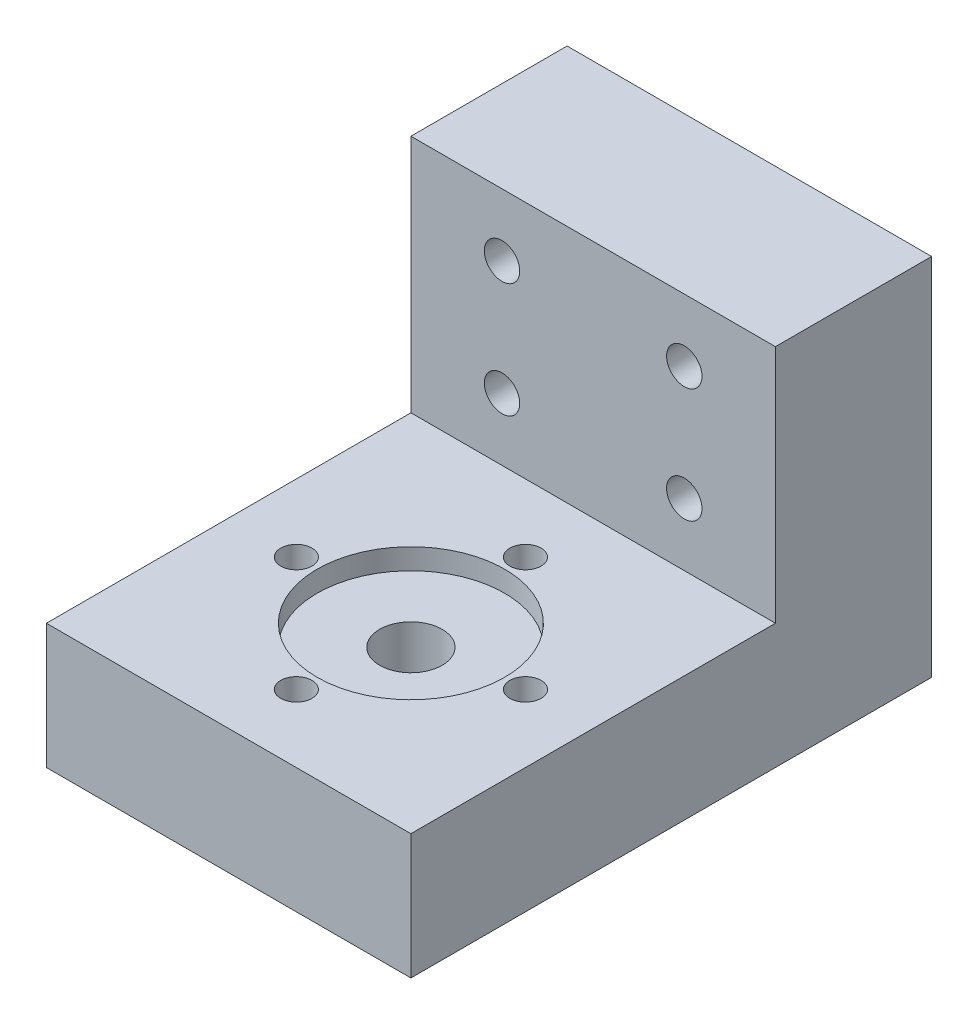
SolidWorks part; units mm, degrees
material "PET"
ref_plane "Front Plane" through (0, 0, 0) normal (0, 0, 1) x (1, 0, 0)
ref_plane "Top Plane" through (0, 0, 0) normal (0, 1, 0) x (1, 0, 0)
ref_plane "Right Plane" through (0, 0, 0) normal (1, 0, 0) x (0, 0, -1)
sketch "Sketch2" plane through (0, 0, 0) normal (0, 0, 1) x (1, 0, 0)
  line L1 (-17.5, -17.5) -> (17.5, -17.5)
  line L2 (-17.5, -17.5) -> (-17.5, 17.5)
  line L3 (-17.5, 17.5) -> (17.5, 17.5)
  line L4 (17.5, -17.5) -> (17.5, 17.5)
  line L5 (-17.5, -17.5) -> (17.5, 17.5) construction
  line L6 (-17.5, 17.5) -> (17.5, -17.5) construction
  point P0 (0, 0)
  dimension "D1" = 35
  dimension "D2" = 35
extrude "Boss-Extrude1" add sketch "Sketch2" along normal blind 15
sketch "Sketch3" plane through (0, 0, 15) normal (0, 0, 1) x (1, 0, 0)
  line L0 (17.5, -17.5) -> (17.5, 17.5) construction
  line L1 (-17.5, -17.5) -> (17.5, -17.5)
  line L2 (-17.5, -17.5) -> (-17.5, -5.5)
  line L3 (-17.5, -5.5) -> (17.5, -5.5)
  line L4 (17.5, -17.5) -> (17.5, -5.5)
  dimension "D1" = 12
extrude "Boss-Extrude2" add sketch "Sketch3" along normal blind 35
sketch "Sketch4" plane through (0, -5.5, 0) normal (0, 1, 0) x (1, 0, 0)
  circle A0 centre (0, -32.5) radius 9
  dimension "D1" = 18
extrude "Cut-Extrude1" cut sketch "Sketch4" against normal blind 2
sketch "Sketch5" plane through (0, -7.5, 0) normal (0, 1, 0) x (1, 0, 0)
  circle A0 centre (0, -32.5) radius 3
  dimension "D1" = 6
extrude "Cut-Extrude2" cut sketch "Sketch5" against normal blind 14
sketch "Sketch6" plane through (0, -5.5, 0) normal (0, 1, 0) x (1, 0, 0)
  line L0 (-11, -32.5) -> (11, -32.5) construction
  line L1 (0, -21.5) -> (0, -43.5) construction
  circle A0 centre (0, -32.5) radius 11 construction
  circle A1 centre (0, -21.5) radius 1.5
  circle A2 centre (0, -43.5) radius 1.5
  circle A3 centre (-11, -32.5) radius 1.5
  circle A4 centre (11, -32.5) radius 1.5
  dimension "D1" = 22
  dimension "D2" = 3
  dimension "D3" = 3
  dimension "D4" = 3
extrude "Cut-Extrude3" cut sketch "Sketch6" against normal through all
sketch "Sketch8" plane through (0, 0, 15) normal (0, 0, 1) x (1, 0, 0)
  line L0 (17.5, -5.5) -> (17.5, 17.5) construction
  line L2 (-17.5, 17.5) -> (-17.5, -5.5) construction
  line L3 (17.5, -5.5) -> (-17.5, -5.5) construction
  line L4 (17.5, 17.5) -> (-17.5, 17.5) construction
  circle A0 centre (-8.75, 0.5) radius 1.7
  circle A1 centre (8.75, 0.5) radius 1.7
  circle A2 centre (8.75, 11.5) radius 1.7
  circle A3 centre (-8.75, 11.5) radius 1.7
  dimension "D1" = 3.4
  dimension "D2" = 3.4
  dimension "D3" = 3.4
  dimension "D4" = 3.4
  dimension "D5" = 8.75
  dimension "D6" = 8.75
  dimension "D7" = 8.75
  dimension "D8" = 8.75
  dimension "D9" = 6
  dimension "D10" = 6
  dimension "D11" = 6
  dimension "D12" = 6
extrude "Cut-Extrude4" cut sketch "Sketch8" against normal through all
